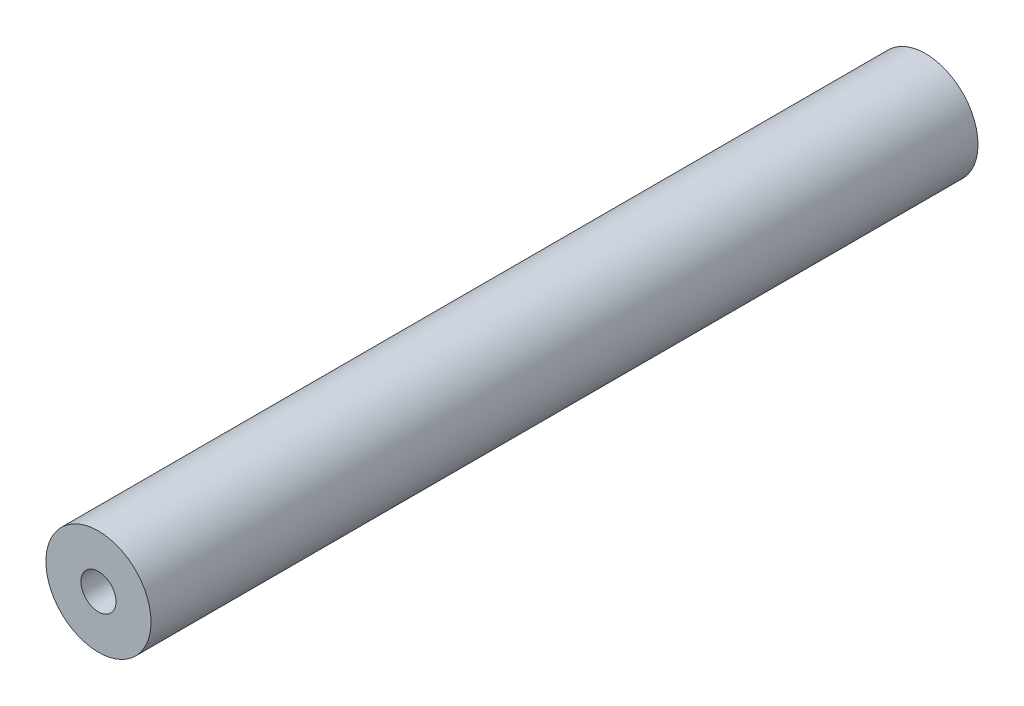
SolidWorks part; units mm, degrees
material "AISI 4140 Steel, quenched & tempered"
ref_plane "Front Plane" through (0, 0, 0) normal (1, 0, 0) x (0, 1, 0)
ref_plane "Top Plane" through (0, 0, 0) normal (0, 0, 1) x (0, 1, 0)
ref_plane "Right Plane" through (0, 0, 0) normal (0, 1, 0) x (-1, 0, 0)
sketch "Sketch1" plane through (0, 0, 0) normal (0, 0, 1) x (0, 1, 0)
  circle A0 centre (0, 0) radius 15
  circle A1 centre (0, 0) radius 5
  dimension "D1" = 10
  dimension "D2" = 30
extrude "Boss-Extrude1" add sketch "Sketch1" against normal mid plane 236
